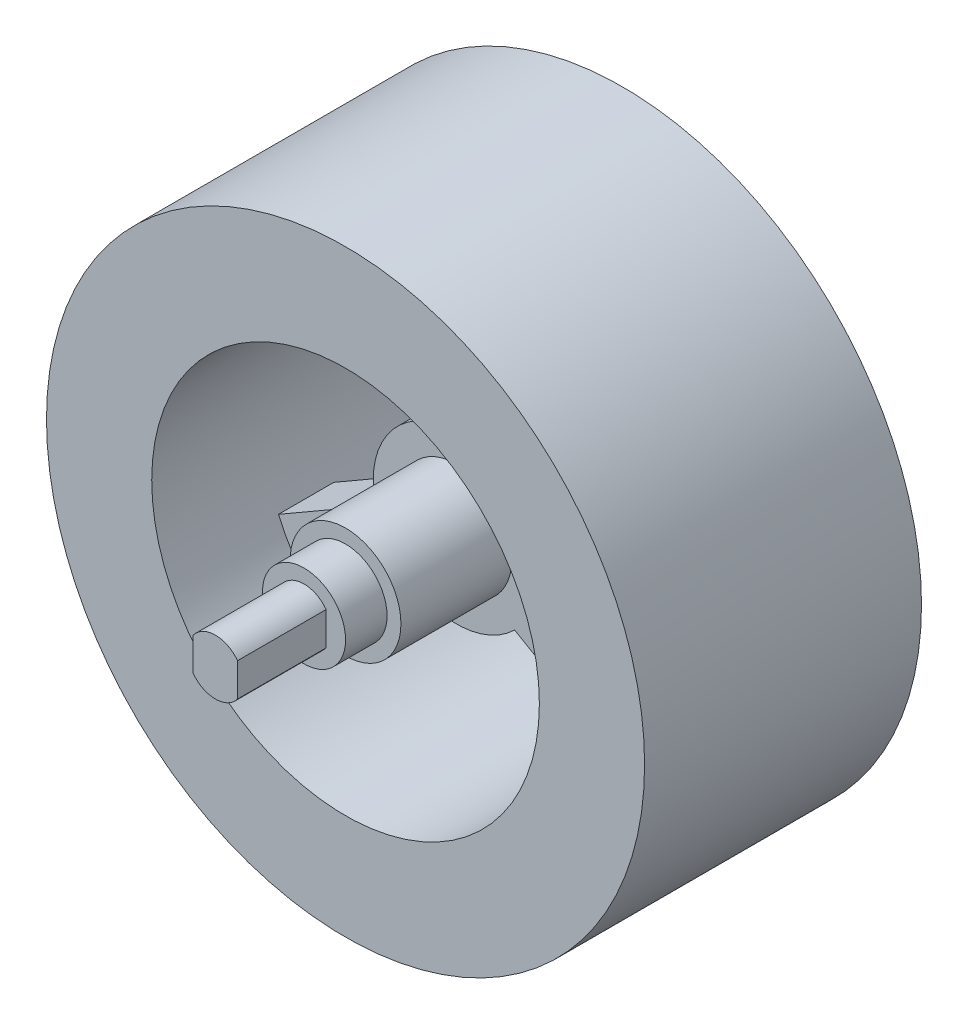
SolidWorks part; units mm, degrees
ref_plane "Front Plane" through (0, 0, 0) normal (0, 0, 1) x (1, 0, 0)
ref_plane "Top Plane" through (0, 0, 0) normal (0, 1, 0) x (1, 0, 0)
ref_plane "Right Plane" through (0, 0, 0) normal (1, 0, 0) x (0, 0, -1)
sketch "Sketch1" plane through (0, 0, 0) normal (0, 0, 1) x (1, 0, 0)
  circle A0 centre (0, 0) radius 7.5
  dimension "D1" = 15
extrude "Boss-Extrude1" add sketch "Sketch1" along normal mid plane 65 contours A0
sketch "Sketch3" plane through (0, 0, 0) normal (0, 0, 1) x (1, 0, 0)
  circle A0 centre (0, 0) radius 5
  dimension "D1" = 10
extrude "Boss-Extrude3" add sketch "Sketch3" along normal mid plane 97
sketch "Sketch4" plane through (0, 0, 0) normal (0, 0, 1) x (1, 0, 0)
  circle A0 centre (0, 0) radius 54
  circle A1 centre (0, 0) radius 35
  dimension "D1" = 108
  dimension "D2" = 70
extrude "Boss-Extrude4" add sketch "Sketch4" along normal mid plane 50
sketch "Sketch5" plane through (0, 0, 0) normal (0, 0, 1) x (1, 0, 0)
  line L0 (14.52, -3.7643) -> (10.52, -10.6925)
  line L1 (-4, 14.4568) -> (4, 14.4568)
  line L2 (-4, 14.4568) -> (-4, 35)
  line L3 (-4, 35) -> (4, 35)
  line L4 (4, 14.4568) -> (4, 35)
  line L5 (14.52, -3.7643) -> (32.3109, -14.0359)
  line L6 (32.3109, -14.0359) -> (28.3109, -20.9641)
  line L7 (10.52, -10.6925) -> (28.3109, -20.9641)
  line L8 (-10.52, -10.6925) -> (-14.52, -3.7643)
  line L9 (-10.52, -10.6925) -> (-28.3109, -20.9641)
  line L10 (-28.3109, -20.9641) -> (-32.3109, -14.0359)
  line L11 (-14.52, -3.7643) -> (-32.3109, -14.0359)
  line L12 (0, 0) -> (4, 14.4568) construction
  circle A0 centre (0, 0) radius 15
  circle A1 centre (0, 0) radius 35 construction
  dimension "D1" = 30
  dimension "D2" = 8
  dimension "D3" = 3
extrude "Boss-Extrude5" add sketch "Sketch5" along normal mid plane 10
sketch "Sketch6" plane through (0, 0, 0) normal (0, 0, 1) x (1, 0, 0)
  circle A0 centre (0, 0) radius 10
  dimension "D1" = 20
extrude "Boss-Extrude6" add sketch "Sketch6" along normal mid plane 50
sketch "Sketch7" plane through (0, 0, -48.5) normal (0, 0, -1) x (-1, 0, 0)
  line L1 (4, 3) -> (5, 3)
  line L2 (4, 3) -> (4, -3)
  line L3 (4, -3) -> (5, -3)
  line L4 (5, 3) -> (5, -3)
  line L5 (-4, 3) -> (-5, 3)
  line L6 (-4, 3) -> (-4, -3)
  line L7 (-4, -3) -> (-5, -3)
  line L8 (-5, 3) -> (-5, -3)
  circle A0 centre (0, 0) radius 5 construction
  circle A1 centre (0, 0) radius 5 construction
  dimension "D1" = 8
extrude "Cut-Extrude1" cut sketch "Sketch7" against normal blind 16
mirror "Mirror1" about plane through (0, 0, 0) normal (0, 0, 1) of "Cut-Extrude1"
sketch "Sketch8" plane through (0, 0, -48.5) normal (0, 0, -1) x (-1, 0, 0)
  circle A0 centre (0, 0) radius 3
  dimension "D1" = 6
extrude "Cut-Extrude2" cut sketch "Sketch8" against normal up to surface (48.5 mm away)
